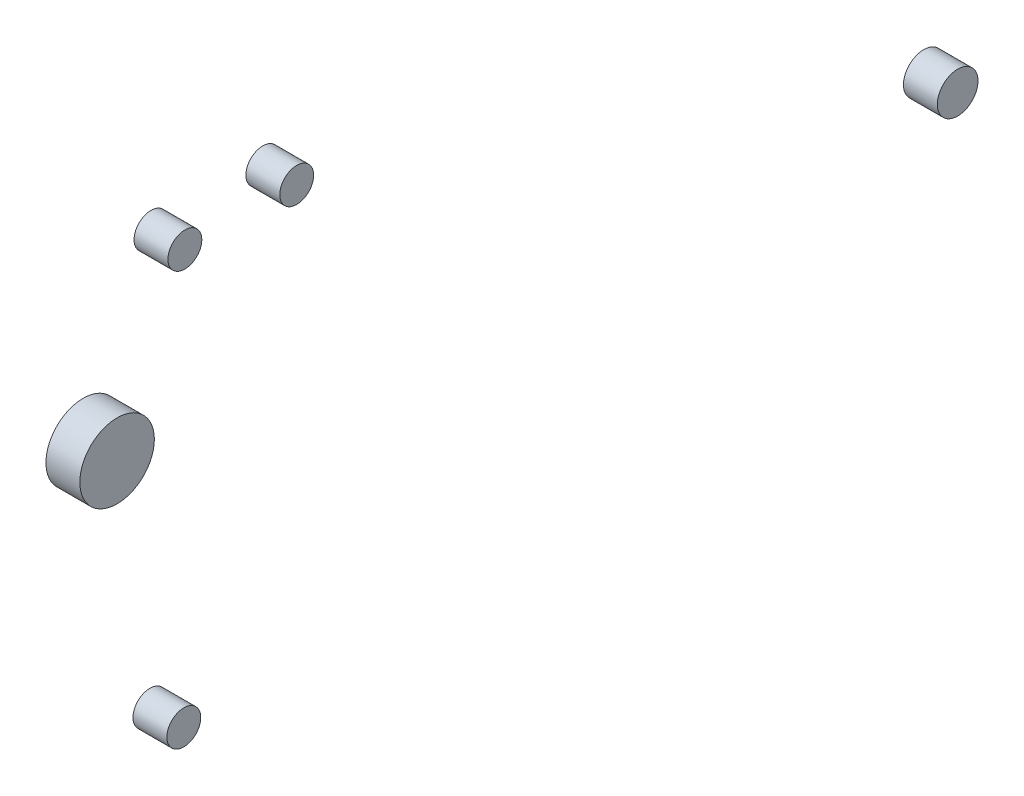
SolidWorks part; units mm, degrees
ref_plane "Front Plane" through (0, 0, 0) normal (0, 0, 1) x (1, 0, 0)
ref_plane "Top Plane" through (0, 0, 0) normal (0, 1, 0) x (1, 0, 0)
ref_plane "Right Plane" through (0, 0, 0) normal (1, 0, 0) x (0, 0, -1)
sketch "Sketch1" plane through (0, 0, 0) normal (1, 0, 0) x (0, 0, -1)
  circle A0 centre (0, 0) radius 1.27
  circle A1 centre (-5, 19.8) radius 2.794
  circle A2 centre (58, 12.2) radius 1.524
  circle A3 centre (0.08, 30.976) radius 1.27
  circle A4 centre (8.462, 30.976) radius 1.27
  point P11 (0, 0)
  dimension "D1" = 2.54
  dimension "D2" = 5.588
  dimension "D5" = 3.048
  dimension "D11" = 2.54
  dimension "D3" = 19.8
  dimension "D4" = 5
  dimension "D6" = 58
  dimension "D7" = 12.2
  dimension "D8" = 11.176
  dimension "D9" = 5.08
  dimension "D10" = 8.382
extrude "Boss-Extrude1" add sketch "Sketch1" along normal blind 2.54
